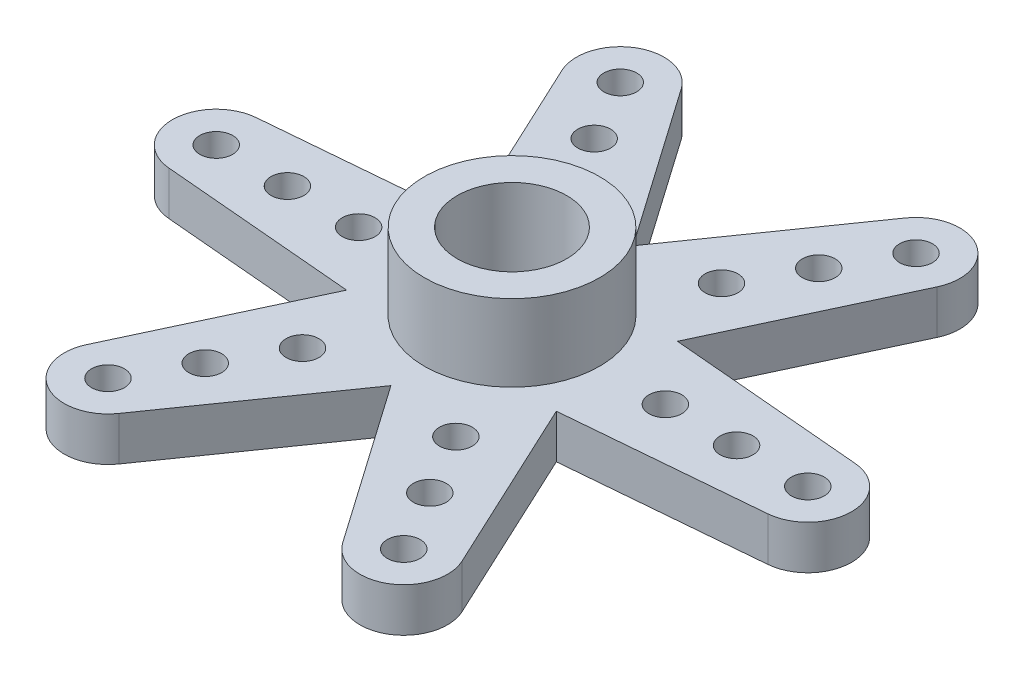
SolidWorks part; units mm, degrees
ref_plane "Plano frontal" through (0, 0, 0) normal (0, 0, 1) x (1, 0, 0)
ref_plane "Plano superior" through (0, 0, 0) normal (0, 1, 0) x (1, 0, 0)
ref_plane "Plano direito" through (0, 0, 0) normal (1, 0, 0) x (0, 0, -1)
sketch "Esboço2" plane through (0, 0, 0) normal (0, 1, 0) x (1, 0, 0)
  line L0 (0, 0) -> (-7, 0) construction
  line L1 (-4.1284, 2.8208) -> (-4.1284, -2.8208) construction
  line L2 (-13.6729, 1.9925) -> (-4.1284, 2.8208)
  line L3 (-13.6729, -1.9925) -> (-4.1284, -2.8208)
  line L4 (-7, 0) -> (-10.25, 0) construction
  line L5 (-10.25, 0) -> (-13.5, 0) construction
  circle A0 centre (0, 0) radius 0.75
  circle A1 centre (-7, 0) radius 0.75
  circle A2 centre (-10.25, 0) radius 0.75
  circle A3 centre (-13.5, 0) radius 0.75
  arc A4 (-4.1284, 2.8208) -> (-4.1284, -2.8208) centre (0, 0) ccw construction
  arc A5 (-4.1284, -2.8208) -> (-4.1284, 2.8208) centre (0, 0) ccw
  arc A6 (-13.6729, 1.9925) -> (-13.6729, -1.9925) centre (-13.5, 0) ccw
  point P0 (-10.089, 0)
  point P14 (-5.6, 0)
  dimension "D2" = 2
  dimension "D3" = 1.5
  dimension "D4" = 5
  dimension "D5" = 1.5
  dimension "D1" = 7
  dimension "D6" = 13.5
  dimension "D8" = 5.6415
extrude "Ressalto-extrusão1" add sketch "Esboço2" along normal blind 2
pattern_circular "PadrãoCircular1" count 6 over 360 about axis through (0, 0, 0) along (0, 1, 0) of "Ressalto-extrusão1"
sketch "Esboço3" plane through (0, 2, 0) normal (0, 1, 0) x (1, 0, 0)
  circle A0 centre (0, 0) radius 4
  circle A2 centre (0, 0) radius 2.5
  dimension "D1" = 8
  dimension "D2" = 5
extrude "Ressalto-extrusão2" add sketch "Esboço3" along normal blind 3.5
sketch "Esboço4" plane through (0, 2, 0) normal (0, 1, 0) x (1, 0, 0)
  circle A0 centre (0, 0) radius 0.75 construction
  circle A1 centre (0, 0) radius 2.5
  circle A2 centre (0, 0) radius 2.5
  circle A3 centre (0, 0) radius 0.75
  dimension "D1" = 0
extrude "Corte-extrusão1" cut sketch "Esboço4" against normal blind 1
sketch "Esboço5" plane through (0, 0, 0) normal (0, -1, 0) x (1, 0, 0)
  circle A0 centre (0, 0) radius 2.5
  circle A1 centre (0, 0) radius 3
  circle A2 centre (0, 0) radius 2.5 construction
  dimension "D1" = 0.5
extrude "Ressalto-extrusão3" add sketch "Esboço5" along normal blind 1
